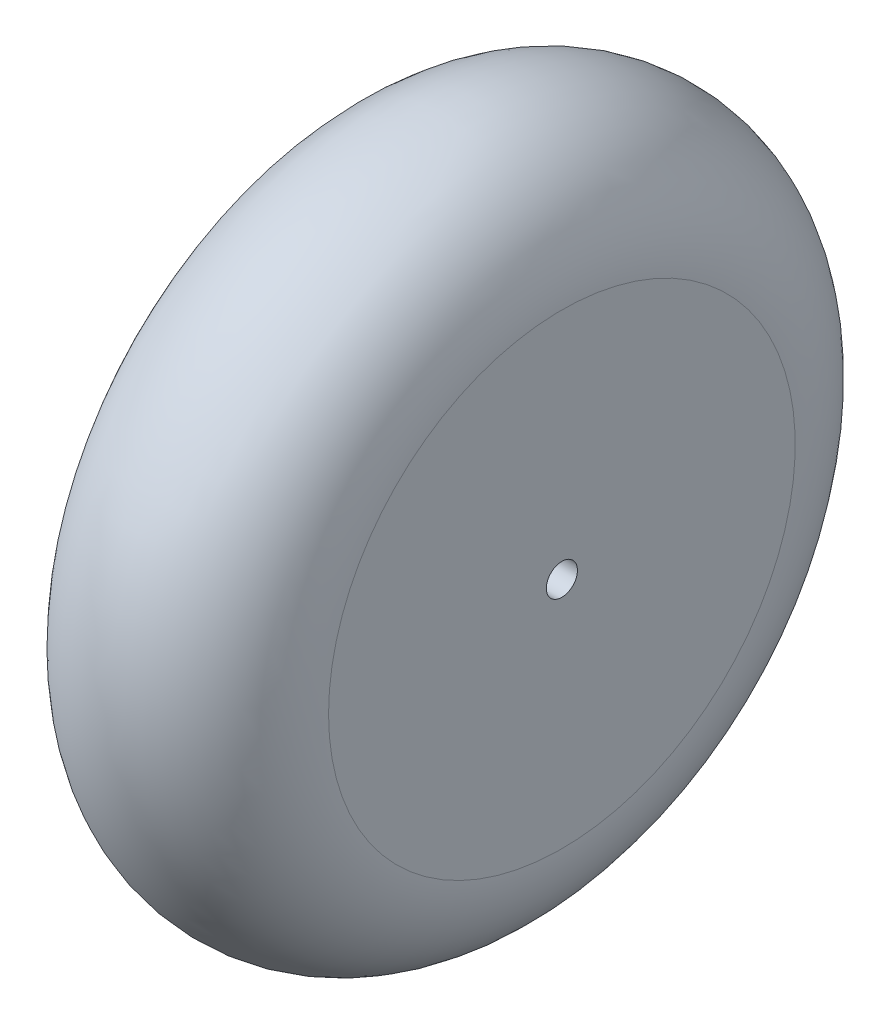
SolidWorks part; units mm, degrees
ref_plane "Front Plane" through (0, 0, 0) normal (0, 0, 1) x (1, 0, 0)
ref_plane "Top Plane" through (0, 0, 0) normal (0, 1, 0) x (1, 0, 0)
ref_plane "Right Plane" through (0, 0, 0) normal (1, 0, 0) x (0, 0, -1)
sketch "Sketch1" plane through (0, 0, 0) normal (0, 0, 1) x (1, 0, 0)
  line L1 (0, 0) -> (30, 0)
  line L2 (0, 0) -> (0, 30)
  line L4 (30, 0) -> (30, 30)
  arc A0 (0, 30) -> (30, 30) centre (15, 30) cw
  dimension "D1" = 45
  dimension "D2" = 30
revolve "Revolve1" add sketch "Sketch1" angle 360 about L1
sketch "Sketch2" plane through (30, 0, 0) normal (1, 0, 0) x (0, 0, -1)
  circle A0 centre (0, 0) radius 2
  dimension "D1" = 4
extrude "Cut-Extrude1" cut sketch "Sketch2" against normal through all
